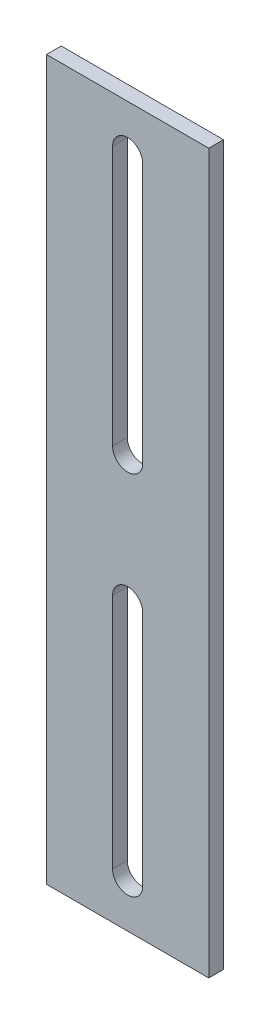
SolidWorks part; units mm, degrees
ref_plane "Alzado" through (0, 0, 0) normal (0, 0, 1) x (1, 0, 0)
ref_plane "Planta" through (0, 0, 0) normal (0, 1, 0) x (1, 0, 0)
ref_plane "Vista lateral" through (0, 0, 0) normal (1, 0, 0) x (0, 0, -1)
sketch "Croquis1" plane through (0, 0, 0) normal (0, 0, 1) x (1, 0, 0)
  line L0 (0, 155) -> (0, -155) construction
  line L1 (35, -155) -> (-35, -155)
  line L2 (35, -155) -> (35, 155)
  line L3 (35, 155) -> (-35, 155)
  line L4 (-35, -155) -> (-35, 155)
  line L5 (35, -155) -> (-35, 155) construction
  line L6 (35, 155) -> (-35, -155) construction
  line L7 (0, 135) -> (0, 22.9971) construction
  line L8 (6.5, 135) -> (6.5, 22.9971)
  line L9 (-6.5, 135) -> (-6.5, 22.9971)
  line L10 (0, -135) -> (0, -32.8013) construction
  line L11 (-6.5, -135) -> (-6.5, -32.8013)
  line L12 (6.5, -135) -> (6.5, -32.8013)
  arc A0 (6.5, 135) -> (-6.5, 135) centre (0, 135) ccw
  arc A1 (-6.5, 22.9971) -> (6.5, 22.9971) centre (0, 22.9971) ccw
  arc A2 (-6.5, -135) -> (6.5, -135) centre (0, -135) ccw
  arc A3 (6.5, -32.8013) -> (-6.5, -32.8013) centre (0, -32.8013) ccw
  point P7 (0, -135)
  point P8 (0, 135)
  point P11 (0, 78.9985)
  point P17 (0, -83.9006)
  point P24 (0, 0)
  point P25 (0, 135)
  point P26 (0, 0)
  dimension "D3" = 135
  dimension "D5" = 6.5
  dimension "D6" = 6.5
  dimension "D1" = 70
  dimension "D2" = 310
  dimension "D4" = 135
extrude "Saliente-Extruir1" add sketch "Croquis1" along normal blind 6.35
